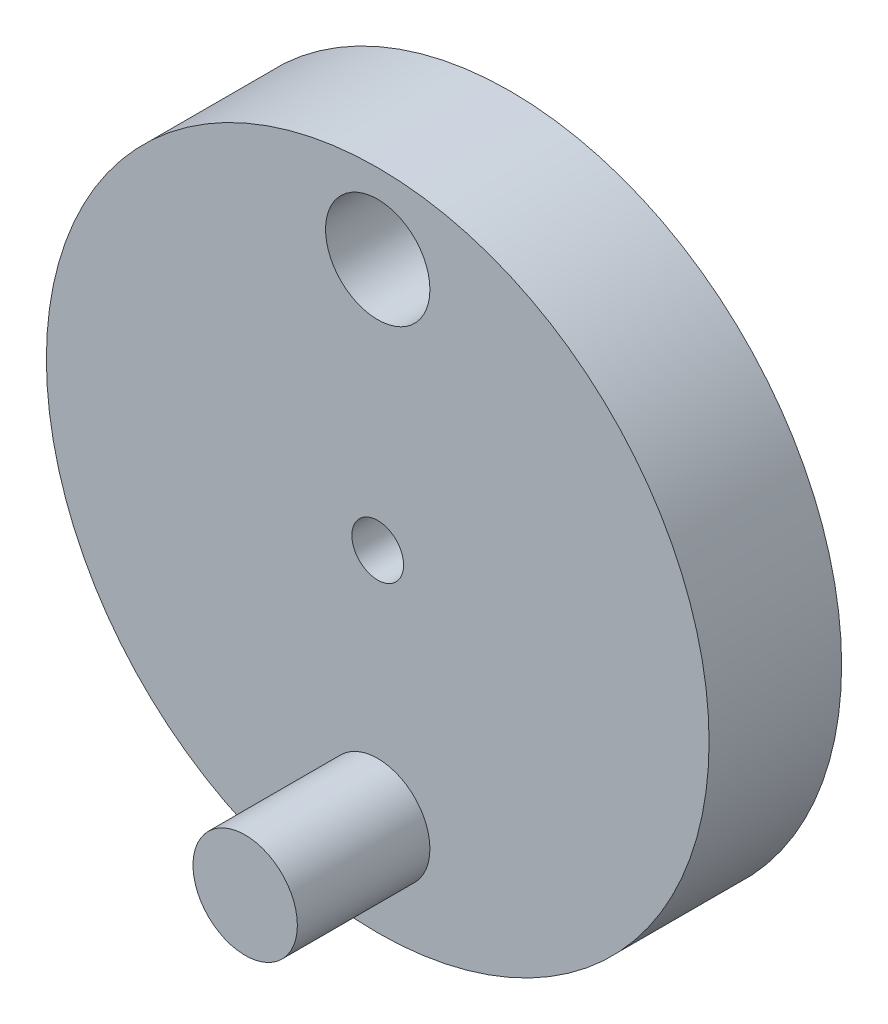
SolidWorks part; units mm, degrees
ref_plane "Front Plane" through (0, 0, 0) normal (0, 0, 1) x (1, 0, 0)
ref_plane "Top Plane" through (0, 0, 0) normal (0, 1, 0) x (1, 0, 0)
ref_plane "Right Plane" through (0, 0, 0) normal (1, 0, 0) x (0, 0, -1)
sketch "Sketch1" plane through (0, 0, 0) normal (0, 0, 1) x (1, 0, 0)
  circle A0 centre (0, 0) radius 12.7
  dimension "D1" = 25.4
extrude "Boss-Extrude1" add sketch "Sketch1" along normal blind 5.08
sketch "Sketch2" plane through (0, 0, 5.08) normal (0, 0, 1) x (1, 0, 0)
  circle A0 centre (0, 0) radius 0.9906
  dimension "D1" = 1.9812
extrude "Cut-Extrude1" cut sketch "Sketch2" against normal through all
sketch "Sketch3" plane through (0, 0, 5.08) normal (0, 0, 1) x (1, 0, 0)
  circle A0 centre (0, 9.652) radius 2
  circle A1 centre (0, 0) radius 0.9906 construction
  dimension "D1" = 9.652
  dimension "D3" = 4
  dimension "D2" = 0
extrude "Cut-Extrude2" cut sketch "Sketch3" against normal through all
sketch "Sketch4" plane through (0, 0, 5.08) normal (0, 0, 1) x (1, 0, 0)
  circle A0 centre (0, -8.9092) radius 2
  dimension "D1" = 4
extrude "Boss-Extrude2" add sketch "Sketch4" along normal blind 5.08
